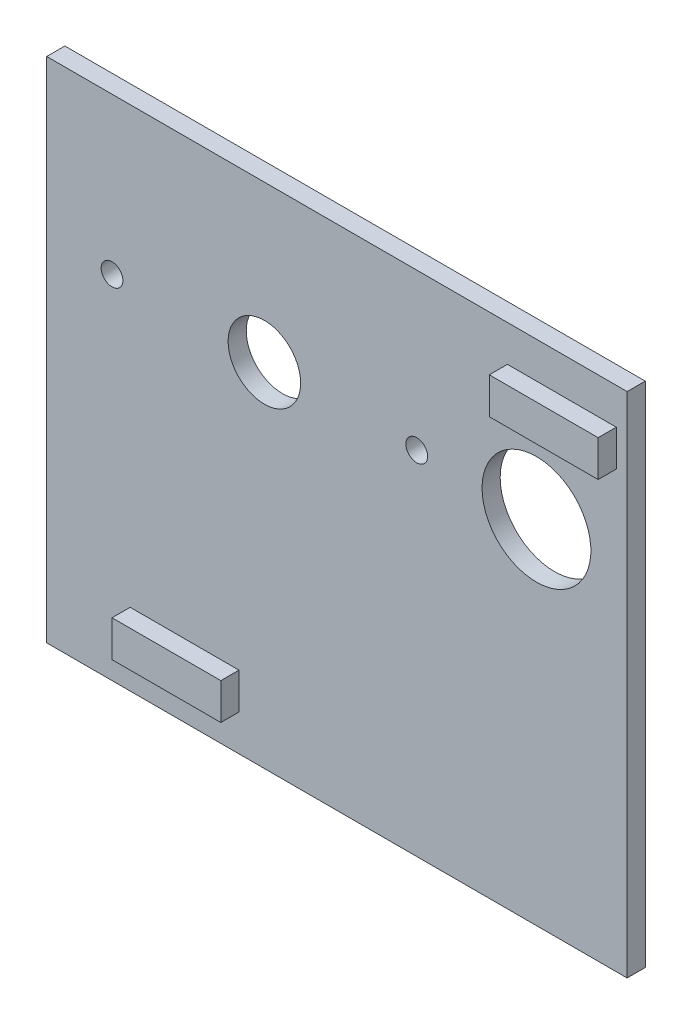
SolidWorks part; units mm, degrees
ref_plane "Front Plane" through (0, 0, 0) normal (0, 0, 1) x (1, 0, 0)
ref_plane "Top Plane" through (0, 0, 0) normal (0, 1, 0) x (1, 0, 0)
ref_plane "Right Plane" through (0, 0, 0) normal (1, 0, 0) x (0, 0, -1)
sketch "Sketch1" plane through (0, 0, 0) normal (0, 0, 1) x (1, 0, 0)
  line L1 (0, 0) -> (-160, 0)
  line L2 (0, 0) -> (0, -140)
  line L3 (0, -140) -> (-160, -140)
  line L4 (-160, 0) -> (-160, -140)
  dimension "D1" = 160
  dimension "D2" = 140
extrude "Boss-Extrude1" add sketch "Sketch1" along normal blind 5
sketch "Sketch2" plane through (0, 0, 5) normal (0, 0, 1) x (1, 0, 0)
  line L0 (-160, -140) -> (0, -140) construction
  line L1 (-33, -10) -> (-3, -10)
  line L2 (-33, -10) -> (-33, -20)
  line L3 (-33, -20) -> (-3, -20)
  line L4 (-3, -10) -> (-3, -20)
  line L7 (0, 0) -> (-160, 0) construction
  line L8 (-160, 0) -> (-160, -140) construction
  line L9 (0, -140) -> (0, 0) construction
  line L12 (-137, -120) -> (-107, -120)
  line L13 (-137, -120) -> (-137, -130)
  line L14 (-137, -130) -> (-107, -130)
  line L15 (-107, -120) -> (-107, -130)
  dimension "D1" = 30
  dimension "D2" = 3
  dimension "D3" = 10
  dimension "D4" = 10
  dimension "D5" = 23
  dimension "D6" = 30
  dimension "D7" = 10
  dimension "D8" = 10
extrude "Boss-Extrude2" add sketch "Sketch2" along normal blind 5
sketch "Sketch4" plane through (0, 0, 10) normal (0, 0, 1) x (1, 0, 0)
  line L0 (0, 0) -> (-160, 0) construction
  line L1 (0, 0) -> (-160, 0) construction
  line L2 (-160, 0) -> (-160, -140) construction
  line L3 (0, -140) -> (0, 0) construction
  circle A0 centre (-142, -43) radius 3
  circle A1 centre (-100, -43) radius 10
  circle A2 centre (-58, -43) radius 3
  circle A3 centre (-25, -43) radius 15
  dimension "D1" = 6
  dimension "D2" = 20
  dimension "D3" = 6
  dimension "D4" = 43
  dimension "D5" = 43
  dimension "D6" = 43
  dimension "D7" = 18
  dimension "D8" = 60
  dimension "D9" = 102
  dimension "D10" = 30
  dimension "D11" = 25
  dimension "D12" = 43
extrude "Cut-Extrude1" cut sketch "Sketch4" against normal blind 15
